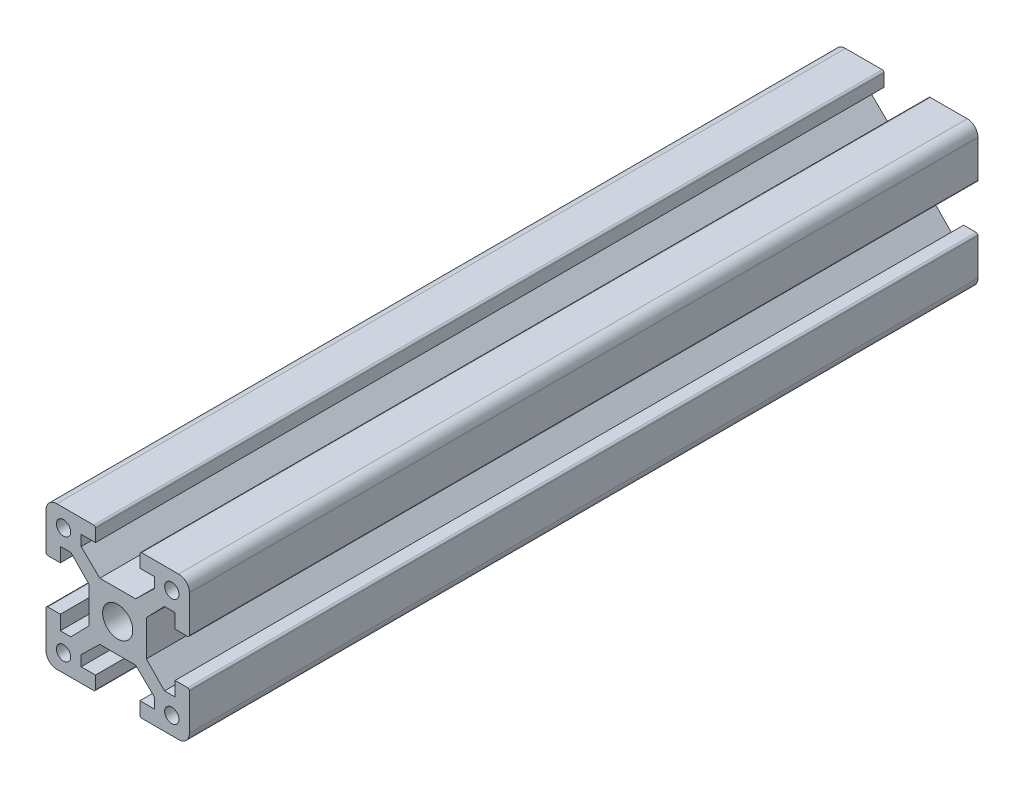
SolidWorks part; units mm, degrees
ref_plane "Front Plane" through (0, 0, 0) normal (0, 0, 1) x (1, 0, 0)
ref_plane "Top Plane" through (0, 0, 0) normal (0, 1, 0) x (1, 0, 0)
ref_plane "Right Plane" through (0, 0, 0) normal (1, 0, 0) x (0, 0, -1)
sketch "Sketch1" plane through (0, 0, 0) normal (0, 0, 1) x (1, 0, 0)
  line L88 (-6.4, -1.5) -> (-6.4, -6.65)
  line L89 (-6.15, -6.9) -> (-4.4, -6.9)
  line L90 (-4.4, -6.9) -> (-4.4, -4.9)
  line L91 (-4.4, -4.9) -> (-2.9278, -4.9)
  line L92 (-2.9278, -4.9) -> (-0.4, -7.5)
  line L93 (-0.4, -7.5) -> (-0.4, -12.5)
  line L94 (-0.4, -12.5) -> (-2.9278, -15.1)
  line L95 (-2.9278, -15.1) -> (-4.4, -15.1)
  line L96 (-4.4, -15.1) -> (-4.4, -13.1)
  line L97 (-4.4, -13.1) -> (-6.15, -13.1)
  line L98 (-6.4, -13.35) -> (-6.4, -18.5)
  line L99 (-4.9, -20) -> (0.25, -20)
  line L100 (0.5, -19.75) -> (0.5, -18)
  line L101 (0.5, -18) -> (-1.5, -18)
  line L102 (-1.5, -18) -> (-1.5, -16.5278)
  line L103 (-1.5, -16.5278) -> (1.1, -14)
  line L104 (1.1, -14) -> (6.1, -14)
  line L105 (6.1, -14) -> (8.7, -16.5278)
  line L106 (8.7, -16.5278) -> (8.7, -18)
  line L107 (8.7, -18) -> (6.7, -18)
  line L108 (6.7, -18) -> (6.7, -19.75)
  line L109 (6.95, -20) -> (12.1, -20)
  line L110 (13.6, -18.5) -> (13.6, -13.35)
  line L111 (13.35, -13.1) -> (11.6, -13.1)
  line L112 (11.6, -13.1) -> (11.6, -15.1)
  line L113 (11.6, -15.1) -> (10.1278, -15.1)
  line L114 (10.1278, -15.1) -> (7.6, -12.5)
  line L115 (7.6, -12.5) -> (7.6, -7.5)
  line L116 (7.6, -7.5) -> (10.1278, -4.9)
  line L117 (10.1278, -4.9) -> (11.6, -4.9)
  line L118 (11.6, -4.9) -> (11.6, -6.9)
  line L119 (11.6, -6.9) -> (13.35, -6.9)
  line L120 (13.6, -6.65) -> (13.6, -1.5)
  line L121 (12.1, 0) -> (6.95, 0)
  line L122 (6.7, -0.25) -> (6.7, -2)
  line L123 (6.7, -2) -> (8.7, -2)
  line L124 (8.7, -2) -> (8.7, -3.4722)
  line L125 (8.7, -3.4722) -> (6.1, -6)
  line L126 (6.1, -6) -> (1.1, -6)
  line L127 (1.1, -6) -> (-1.5, -3.4722)
  line L128 (-1.5, -3.4722) -> (-1.5, -2)
  line L129 (-1.5, -2) -> (0.5, -2)
  line L130 (0.5, -2) -> (0.5, -0.25)
  line L131 (0.25, 0) -> (-4.9, 0)
  circle A0 centre (-3.95, -2.45) radius 1
  circle A1 centre (11.15, -2.45) radius 1
  circle A2 centre (-3.95, -17.55) radius 1
  circle A3 centre (11.15, -17.55) radius 1
  circle A4 centre (3.6, -10) radius 2.1
  arc A26 (-6.4, -6.65) -> (-6.15, -6.9) centre (-6.15, -6.65) ccw
  arc A27 (-6.15, -13.1) -> (-6.4, -13.35) centre (-6.15, -13.35) ccw
  arc A28 (-6.4, -18.5) -> (-4.9, -20) centre (-4.9, -18.5) ccw
  arc A29 (0.25, -20) -> (0.5, -19.75) centre (0.25, -19.75) ccw
  arc A30 (6.7, -19.75) -> (6.95, -20) centre (6.95, -19.75) ccw
  arc A31 (12.1, -20) -> (13.6, -18.5) centre (12.1, -18.5) ccw
  arc A32 (13.6, -13.35) -> (13.35, -13.1) centre (13.35, -13.35) ccw
  arc A33 (13.35, -6.9) -> (13.6, -6.65) centre (13.35, -6.65) ccw
  arc A34 (13.6, -1.5) -> (12.1, 0) centre (12.1, -1.5) ccw
  arc A35 (6.95, 0) -> (6.7, -0.25) centre (6.95, -0.25) ccw
  arc A36 (0.5, -0.25) -> (0.25, 0) centre (0.25, -0.25) ccw
  arc A37 (-4.9, 0) -> (-6.4, -1.5) centre (-4.9, -1.5) ccw
extrude "Boss-Extrude2" add sketch "Sketch1" along normal blind 110
